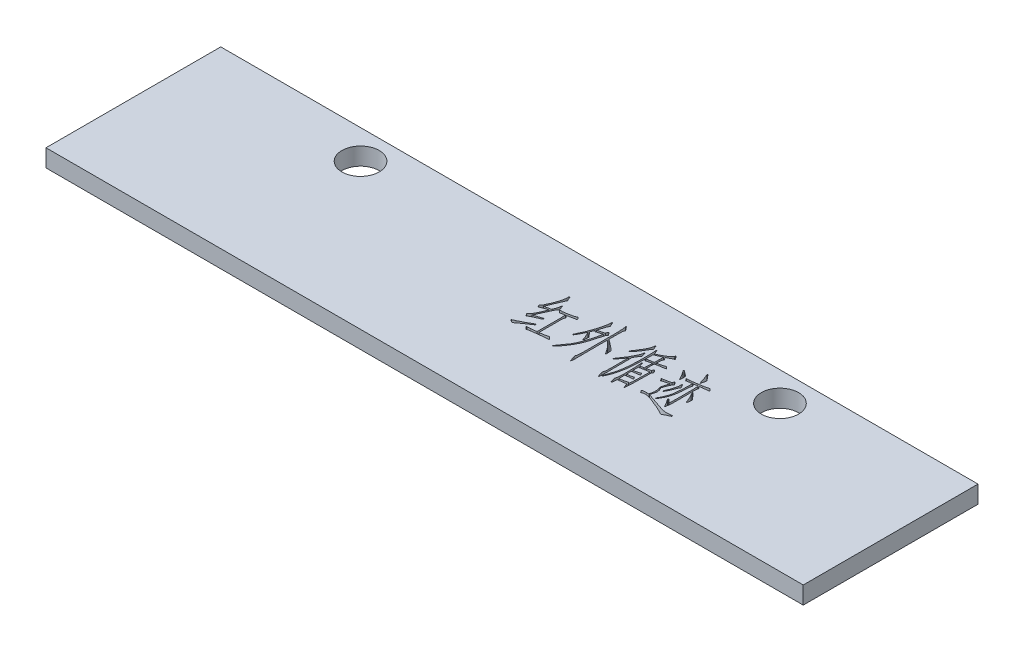
SolidWorks part; units mm, degrees
material "纯金"
ref_plane "前视基准面" through (0, 0, 0) normal (0, 0, 1) x (1, 0, 0)
ref_plane "上视基准面" through (0, 0, 0) normal (0, 1, 0) x (1, 0, 0)
ref_plane "右视基准面" through (0, 0, 0) normal (1, 0, 0) x (0, 0, -1)
sketch "草图1" plane through (0, 0, 0) normal (0, 1, 0) x (1, 0, 0)
  line L1 (-32.5, -7.5) -> (32.5, -7.5)
  line L2 (-32.5, -7.5) -> (-32.5, 7.5)
  line L3 (-32.5, 7.5) -> (32.5, 7.5)
  line L4 (32.5, -7.5) -> (32.5, 7.5)
  line L5 (-32.5, -7.5) -> (32.5, 7.5) construction
  line L6 (-32.5, 7.5) -> (32.5, -7.5) construction
  point P0 (0, 0)
  dimension "D1" = 15
  dimension "D2" = 65
extrude "凸台-拉伸1" add sketch "草图1" along normal blind 1.5
sketch "草图2" plane through (0, 1.5, 0) normal (0, 1, 0) x (1, 0, 0)
  line L0 (-32.5, 7.5) -> (-32.5, -7.5) construction
  line L1 (32.5, 7.5) -> (-32.5, 7.5) construction
  circle A0 centre (-18, 5) radius 1.6
  dimension "D1" = 3.2
  dimension "D2" = 14.5
  dimension "D3" = 2.5
extrude "切除-拉伸1" cut sketch "草图2" against normal blind 1.5
ref_plane "基准面1" through (0, 0, 0) normal (-1, 0, 0) x (0, 0, 1)
mirror "镜向1" about plane through (0, 0, 0) normal (-1, 0, 0) of "切除-拉伸1"
sketch "草图3" plane through (0, 1.5, 0) normal (0, 1, 0) x (1, 0, 0)
  text T0 "红外循迹"
extrude "切除-拉伸4" cut sketch "草图3" against normal through all
